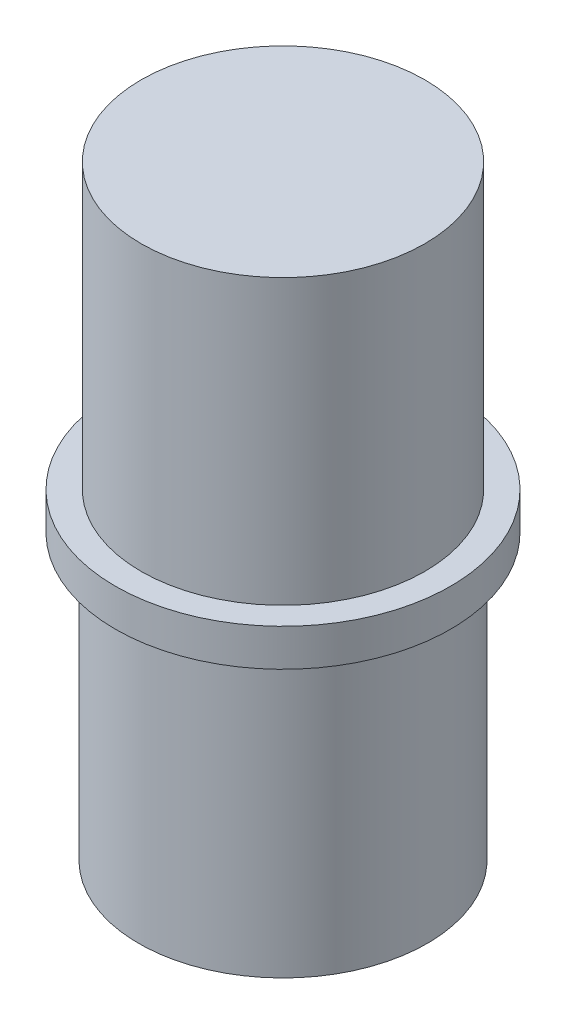
SolidWorks part; units mm, degrees
ref_plane "Front Plane" through (0, 0, 0) normal (0, 0, 1) x (1, 0, 0)
ref_plane "Top Plane" through (0, 0, 0) normal (0, 1, 0) x (1, 0, 0)
ref_plane "Right Plane" through (0, 0, 0) normal (1, 0, 0) x (0, 0, -1)
sketch "Sketch1" plane through (0, 0, 0) normal (0, 1, 0) x (1, 0, 0)
  circle A0 centre (0, 0) radius 3.8735
  dimension "D1" = 7.747
extrude "Boss-Extrude1" add sketch "Sketch1" along normal blind 7.62
sketch "Sketch2" plane through (0, 7.62, 0) normal (0, 1, 0) x (1, 0, 0)
  circle A0 centre (0, 0) radius 4.5
  dimension "D1" = 9
extrude "Boss-Extrude2" add sketch "Sketch2" along normal blind 1
sketch "Sketch3" plane through (0, 8.62, 0) normal (0, 1, 0) x (1, 0, 0)
  circle A0 centre (0, 0) radius 3.81
  dimension "D1" = 7.62
extrude "Boss-Extrude3" add sketch "Sketch3" along normal blind 7.62
